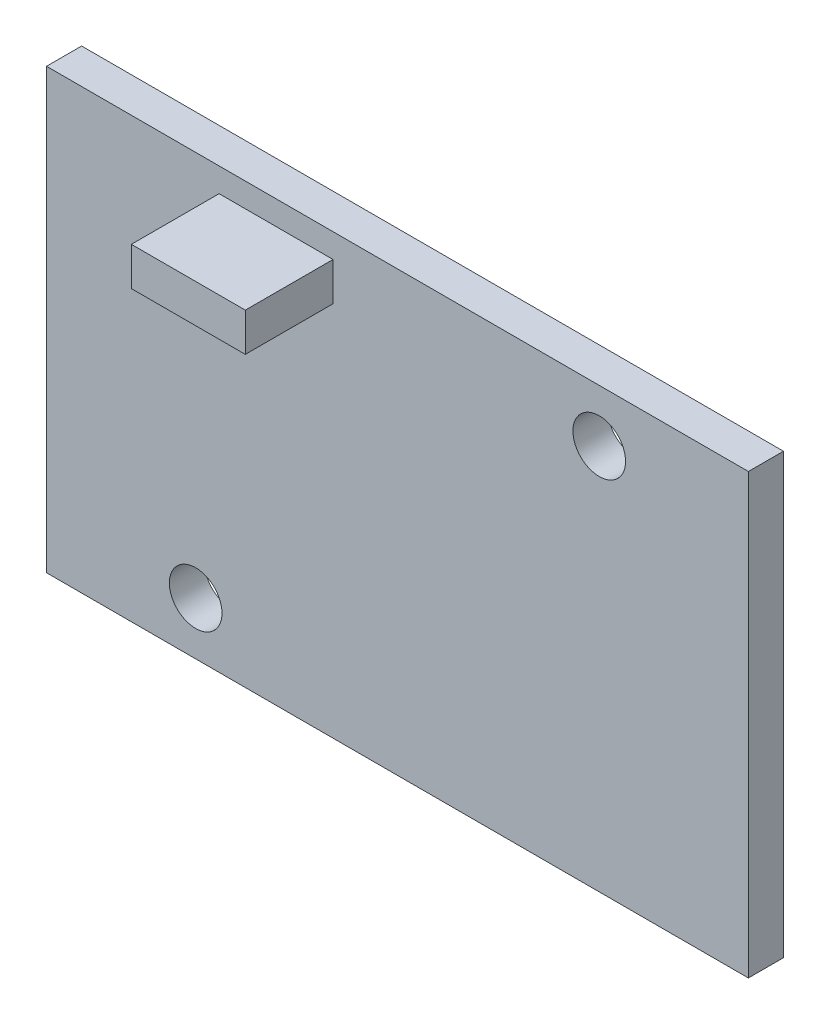
SolidWorks part; units mm, degrees
ref_plane "Alzado" through (0, 0, 0) normal (0, 0, 1) x (1, 0, 0)
ref_plane "Planta" through (0, 0, 0) normal (0, 1, 0) x (1, 0, 0)
ref_plane "Vista lateral" through (0, 0, 0) normal (1, 0, 0) x (0, 0, -1)
sketch "Croquis1" plane through (0, 0, 0) normal (0, 0, 1) x (1, 0, 0)
  line L1 (-27.7518, 20.0575) -> (12.2482, 20.0575)
  line L2 (-27.7518, 20.0575) -> (-27.7518, -4.9425)
  line L3 (-27.7518, -4.9425) -> (12.2482, -4.9425)
  line L4 (12.2482, 20.0575) -> (12.2482, -4.9425)
  circle A0 centre (3.7482, 17.0575) radius 1.5
  circle A1 centre (-19.2518, -1.9425) radius 1.5
  dimension "D3" = 3
  dimension "D6" = 3
  dimension "D1" = 40
  dimension "D2" = 25
  dimension "D4" = 8.5
  dimension "D5" = 3
  dimension "D7" = 19
  dimension "D8" = 23
extrude "Saliente-Extruir1" add sketch "Croquis1" along normal blind 2
sketch "Croquis2" plane through (0, 0, 2) normal (0, 0, 1) x (1, 0, 0)
  line L1 (-17.9171, 18.6864) -> (-11.4228, 18.6864)
  line L2 (-17.9171, 18.6864) -> (-17.9171, 16.5014)
  line L3 (-17.9171, 16.5014) -> (-11.4228, 16.5014)
  line L4 (-11.4228, 18.6864) -> (-11.4228, 16.5014)
extrude "Saliente-Extruir2" add sketch "Croquis2" along normal blind 5
